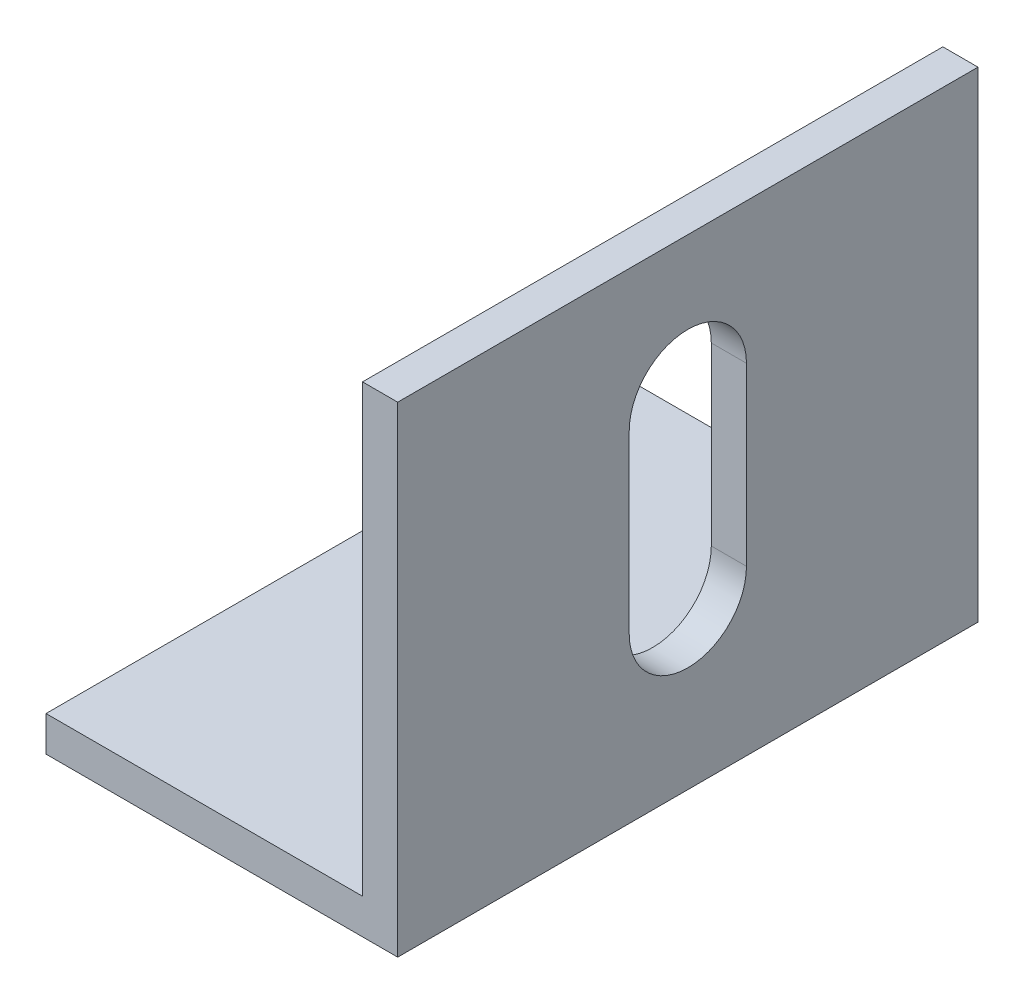
SolidWorks part; units mm, degrees
ref_plane "Front Plane" through (0, 0, 0) normal (0, 0, 1) x (1, 0, 0)
ref_plane "Top Plane" through (0, 0, 0) normal (0, 1, 0) x (1, 0, 0)
ref_plane "Right Plane" through (0, 0, 0) normal (1, 0, 0) x (0, 0, -1)
sketch "Sketch1" plane through (0, 0, 0) normal (0, 0, 1) x (1, 0, 0)
  line L0 (-15.24, 0) -> (0, 0)
  line L1 (-1.524, 1.524) -> (-15.24, 1.524)
  line L2 (-1.524, 1.524) -> (-1.524, 20.828)
  line L3 (-1.524, 20.828) -> (0, 20.828)
  line L4 (0, 20.828) -> (0, 0)
  line L10 (-15.24, 0) -> (-15.24, 1.524)
  dimension "D1" = 20.828
  dimension "D2" = 1.524
  dimension "D3" = 1.524
  dimension "D4" = 15.24
extrude "Boss-Extrude2" add sketch "Sketch1" along normal blind 25.146
sketch "Sketch3" plane through (-1.524, 0, 0) normal (-1, 0, 0) x (0, 0, 1)
  line L0 (12.573, 1.524) -> (12.573, 20.828) construction
  line L1 (25.146, 1.524) -> (0, 1.524) construction
  line L2 (25.146, 20.828) -> (0, 20.828) construction
  line L3 (12.573, 14.732) -> (12.573, 7.112) construction
  line L4 (15.113, 14.732) -> (15.113, 7.112)
  line L5 (10.033, 14.732) -> (10.033, 7.112)
  arc A0 (15.113, 14.732) -> (10.033, 14.732) centre (12.573, 14.732) ccw
  arc A1 (10.033, 7.112) -> (15.113, 7.112) centre (12.573, 7.112) ccw
  point P8 (12.573, 10.922)
  dimension "D1" = 6.096
  dimension "D3" = 2.54
  dimension "D2" = 7.62
extrude "Cut-Extrude1" cut sketch "Sketch3" against normal up to next
sketch "Sketch4" plane through (0, 1.524, 0) normal (0, 1, 0) x (1, 0, 0)
  line L0 (-1.524, -12.573) -> (-15.24, -12.573) construction
  line L1 (-1.524, -25.146) -> (-1.524, 0) construction
  line L2 (-15.24, -25.146) -> (-15.24, 0) construction
  line L3 (-6.731, 0) -> (-6.731, -25.146) construction
  line L4 (-1.524, 0) -> (-15.24, 0) construction
  line L5 (-1.524, -25.146) -> (-15.24, -25.146) construction
  circle A0 centre (-6.731, -12.573) radius 2.54
  dimension "D2" = 5.08
  dimension "D1" = 8.509
extrude "Cut-Extrude2" cut sketch "Sketch4" against normal up to next
